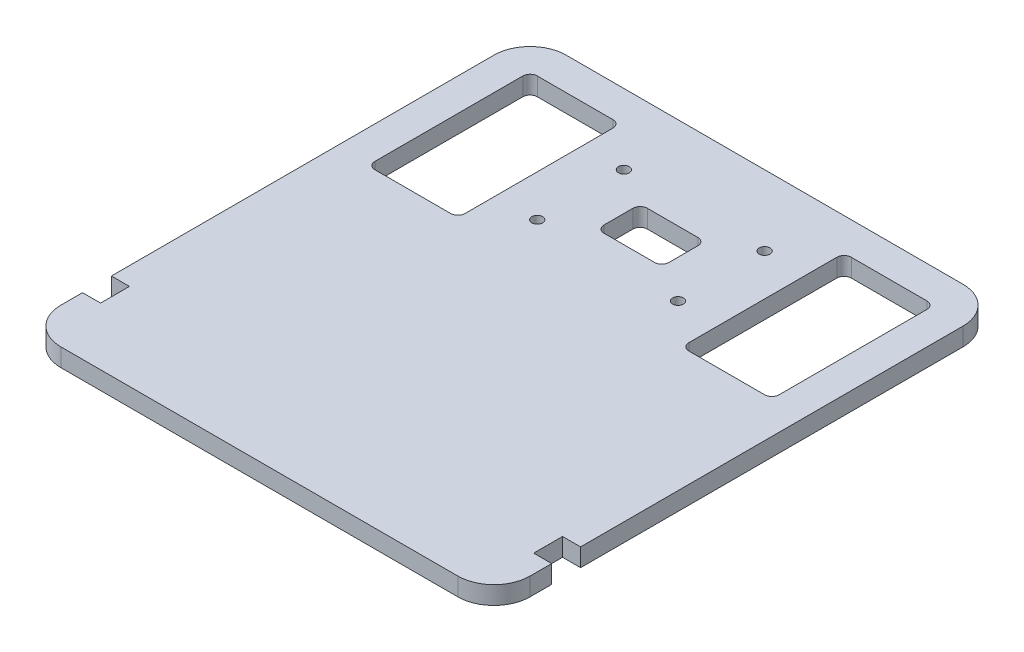
SolidWorks part; units mm, degrees
ref_plane "Plano frontal" through (0, 0, 0) normal (0, 0, 1) x (1, 0, 0)
ref_plane "Plano superior" through (0, 0, 0) normal (0, 1, 0) x (1, 0, 0)
ref_plane "Plano direito" through (0, 0, 0) normal (1, 0, 0) x (0, 0, -1)
sketch "Esboço1" plane through (0, 0, 0) normal (0, 1, 0) x (1, 0, 0)
  line L1 (-43.3361, 103.0246) -> (66.6639, 103.0246)
  line L2 (-53.3361, 93.0246) -> (-53.3361, -26.9754)
  line L3 (-43.3361, -36.9754) -> (66.6639, -36.9754)
  line L4 (76.6639, 93.0246) -> (76.6639, -26.9754)
  arc A0 (76.6639, 93.0246) -> (66.6639, 103.0246) centre (66.6639, 93.0246) ccw
  arc A1 (66.6639, -36.9754) -> (76.6639, -26.9754) centre (66.6639, -26.9754) ccw
  arc A2 (-53.3361, -26.9754) -> (-43.3361, -36.9754) centre (-43.3361, -26.9754) ccw
  arc A3 (-43.3361, 103.0246) -> (-53.3361, 93.0246) centre (-43.3361, 93.0246) ccw
  dimension "D1" = 10
extrude "Ressalto-extrusão1" add sketch "Esboço1" along normal blind 5
sketch "Esboço2" plane through (0, 5, 0) normal (0, 1, 0) x (1, 0, 0)
  line L1 (-42.3361, 94.0246) -> (-21.3361, 94.0246)
  line L2 (-44.3361, 92.0246) -> (-44.3361, 51.0246)
  line L3 (-42.3361, 49.0246) -> (-21.3361, 49.0246)
  line L4 (-19.3361, 92.0246) -> (-19.3361, 51.0246)
  line L5 (66.6639, 103.0246) -> (-43.3361, 103.0246) construction
  line L6 (-53.3361, 93.0246) -> (-53.3361, -26.9754) construction
  line L7 (76.6639, -26.9754) -> (76.6639, 93.0246) construction
  line L8 (44.6639, 94.0246) -> (65.6639, 94.0246)
  line L9 (42.6639, 92.0246) -> (42.6639, 51.0246)
  line L10 (44.6639, 49.0246) -> (65.6639, 49.0246)
  line L11 (67.6639, 92.0246) -> (67.6639, 51.0246)
  arc A0 (-44.3361, 92.0246) -> (-42.3361, 94.0246) centre (-42.3361, 92.0246) cw
  arc A1 (-42.3361, 49.0246) -> (-44.3361, 51.0246) centre (-42.3361, 51.0246) cw
  arc A2 (-21.3361, 49.0246) -> (-19.3361, 51.0246) centre (-21.3361, 51.0246) ccw
  arc A3 (-19.3361, 92.0246) -> (-21.3361, 94.0246) centre (-21.3361, 92.0246) ccw
  arc A4 (42.6639, 92.0246) -> (44.6639, 94.0246) centre (44.6639, 92.0246) cw
  arc A5 (44.6639, 49.0246) -> (42.6639, 51.0246) centre (44.6639, 51.0246) cw
  arc A6 (65.6639, 49.0246) -> (67.6639, 51.0246) centre (65.6639, 51.0246) ccw
  arc A7 (67.6639, 92.0246) -> (65.6639, 94.0246) centre (65.6639, 92.0246) ccw
  point P16 (-44.3361, 94.0246)
  point P19 (-44.3361, 49.0246)
  point P26 (42.6639, 94.0246)
  point P29 (42.6639, 49.0246)
  dimension "D7" = 2
  dimension "D1" = 45
  dimension "D2" = 9
  dimension "D3" = 9
  dimension "D4" = 9
  dimension "D5" = 9
  dimension "D6" = 45
extrude "Corte-extrusão1" cut sketch "Esboço2" against normal blind 5
sketch "Esboço4" plane through (0, 5, 0) normal (0, 1, 0) x (1, 0, 0)
  line L0 (42.6639, 92.0246) -> (42.6639, 51.0246) construction
  line L1 (-19.3361, 51.0246) -> (-19.3361, 92.0246) construction
  line L2 (-21.3361, 94.0246) -> (-42.3361, 94.0246) construction
  line L4 (65.6639, 94.0246) -> (44.6639, 94.0246) construction
  circle A0 centre (-7.8361, 59.5246) radius 1.5
  circle A1 centre (31.1639, 59.5246) radius 1.5
  circle A2 centre (-7.8361, 83.5246) radius 1.5
  circle A3 centre (31.1639, 83.5246) radius 1.5
  dimension "D1" = 24
  dimension "D2" = 24
  dimension "D3" = 11.5
  dimension "D4" = 11.5
  dimension "D5" = 11.5
  dimension "D6" = 11.5
  dimension "D7" = 10.5
  dimension "D8" = 10.5
  dimension "D9" = 3
  dimension "D10" = 3
  dimension "D11" = 3
  dimension "D12" = 3
extrude "Corte-extrusão2" cut sketch "Esboço4" against normal blind 10
sketch "Esboço6" plane through (-53.3361, 0, 0) normal (-1, 0, 0) x (0, 0, 1)
  line L0 (-93.0246, 5) -> (26.9754, 5) construction
  line L1 (20.9754, 5) -> (12.9754, 5)
  line L2 (20.9754, 5) -> (20.9754, 0)
  line L3 (20.9754, 0) -> (12.9754, 0)
  line L4 (12.9754, 5) -> (12.9754, 0)
  line L5 (-93.0246, 0) -> (26.9754, 0) construction
  line L6 (26.9754, 5) -> (26.9754, 0) construction
  dimension "D1" = 6
  dimension "D2" = 8
extrude "Corte-extrusão3" cut sketch "Esboço6" against normal blind 5
sketch "Esboço7" plane through (0, 0, 0) normal (0, -1, 0) x (1, 0, 0)
  line L1 (18.6639, -77.5246) -> (4.6639, -77.5246)
  line L2 (20.6639, -75.5246) -> (20.6639, -67.5246)
  line L3 (18.6639, -65.5246) -> (4.6639, -65.5246)
  line L4 (2.6639, -75.5246) -> (2.6639, -67.5246)
  line L5 (42.6639, -92.0246) -> (42.6639, -51.0246) construction
  line L6 (-19.3361, -51.0246) -> (-19.3361, -92.0246) construction
  circle A0 centre (31.1639, -83.5246) radius 1.5 construction
  circle A1 centre (31.1639, -59.5246) radius 1.5 construction
  arc A2 (2.6639, -75.5246) -> (4.6639, -77.5246) centre (4.6639, -75.5246) ccw
  arc A3 (4.6639, -65.5246) -> (2.6639, -67.5246) centre (4.6639, -67.5246) ccw
  arc A4 (18.6639, -65.5246) -> (20.6639, -67.5246) centre (18.6639, -67.5246) cw
  arc A5 (20.6639, -75.5246) -> (18.6639, -77.5246) centre (18.6639, -75.5246) cw
  dimension "D5" = 2
  dimension "D1" = 6
  dimension "D2" = 6
  dimension "D3" = 22
  dimension "D4" = 22
extrude "Corte-extrusão4" cut sketch "Esboço7" against normal blind 10
ref_plane "Plano1" through (76.6639, 5, 26.9754) normal (0, 0, -1) x (-1, 0, 0)
sketch "Esboço9" plane through (76.6639, 0, 0) normal (1, 0, 0) x (0, 0, -1)
  line L0 (-26.9754, 5) -> (93.0246, 5) construction
  line L1 (-20.9754, 5) -> (-12.9754, 5)
  line L2 (-20.9754, 5) -> (-20.9754, 0)
  line L3 (-20.9754, 0) -> (-12.9754, 0)
  line L4 (-12.9754, 5) -> (-12.9754, 0)
  line L5 (-26.9754, 0) -> (93.0246, 0) construction
  line L6 (-26.9754, 5) -> (-26.9754, 0) construction
  dimension "D1" = 6
  dimension "D2" = 8
extrude "Corte-extrusão5" cut sketch "Esboço9" against normal blind 5
sketch "Esboço10" plane through (0, 5, 0) normal (0, 1, 0) x (1, 0, 0)
  line L0 (1.6639, 64.0246) -> (1.6639, 79.0246)
  line L1 (1.6639, 79.0246) -> (21.6639, 79.0246)
  line L2 (1.6639, 64.0246) -> (21.6639, 64.0246)
  line L3 (42.6639, 92.0246) -> (42.6639, 51.0246) construction
  line L4 (21.6639, 79.0246) -> (21.6639, 64.0246)
  line L5 (-19.3361, 51.0246) -> (-19.3361, 92.0246) construction
  line L7 (66.6639, 103.0246) -> (-43.3361, 103.0246) construction
  line L10 (4.6639, 65.5246) -> (18.6639, 65.5246) construction
  line L11 (-16.3361, 94.0246) -> (-7.3018, 94.0246)
  line L12 (-16.3361, 94.0246) -> (-16.3361, 49.0246)
  line L13 (-16.3361, 49.0246) -> (39.6639, 49.0246)
  line L15 (-7.3018, 94.0246) -> (39.6639, 94.0246)
  line L16 (39.6639, 94.0246) -> (39.6639, 49.0246)
  circle A0 centre (-7.8361, 83.5246) radius 1.5
  circle A1 centre (-7.8361, 59.5246) radius 1.5
  circle A2 centre (31.1639, 59.5246) radius 1.5
  circle A3 centre (31.1639, 83.5246) radius 1.5
  dimension "D1" = 21
  dimension "D2" = 21
  dimension "D3" = 24
  dimension "D4" = 1.5
  dimension "D5" = 3
  dimension "D6" = 3
